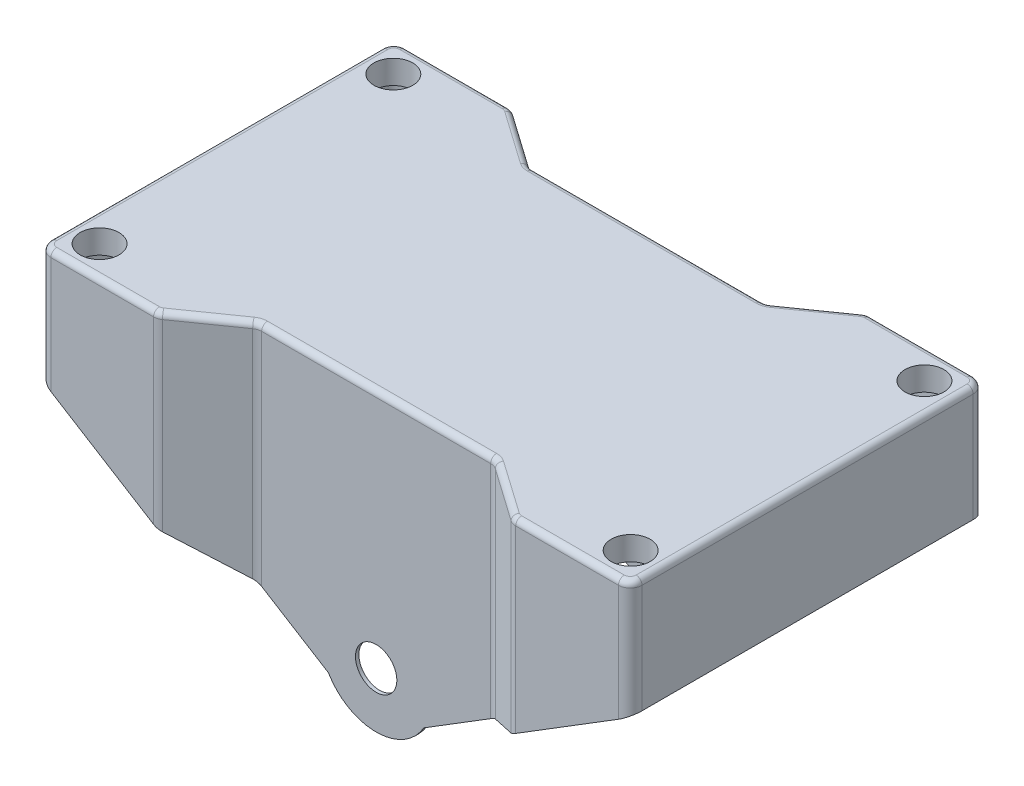
SolidWorks part; units mm, degrees
ref_plane "Front Plane" through (0, 0, 0) normal (0, 0, 1) x (1, 0, 0)
ref_plane "Top Plane" through (0, 0, 0) normal (0, 1, 0) x (1, 0, 0)
ref_plane "Right Plane" through (0, 0, 0) normal (1, 0, 0) x (0, 0, -1)
sketch "Sketch1" plane through (0, 0, 0) normal (0, 1, 0) x (1, 0, 0)
  line L0 (-131.7395, 0) -> (140.8323, 0) construction
  line L1 (0, 62.0007) -> (0, -76.4531) construction
  line L2 (-50, -30) -> (-50, 30)
  line L3 (-50, 30) -> (-30, 30)
  line L4 (-30, 30) -> (-20, 22.9793)
  line L5 (-20, 22.9793) -> (20, 22.9793)
  line L6 (30, 30) -> (20, 22.9793)
  line L7 (50, 30) -> (30, 30)
  line L8 (50, -30) -> (50, 30)
  line L9 (50, -30) -> (30, -30)
  line L10 (30, -30) -> (20, -22.9793)
  line L11 (-20, -22.9793) -> (20, -22.9793)
  line L12 (-30, -30) -> (-20, -22.9793)
  line L13 (-50, -30) -> (-30, -30)
  circle A0 centre (-44.9207, 24.8485) radius 3.2868
  circle A1 centre (-44.9207, -24.8485) radius 3.2868
  circle A2 centre (44.9207, -24.8485) radius 3.2868
  circle A3 centre (44.9207, 24.8485) radius 3.2868
  point P5 (0, -22.9793)
  point P12 (0, 22.9793)
  point P16 (50, 0)
  point P21 (-50, 0)
  dimension "D1" = 50
  dimension "D2" = 20
  dimension "D3" = 20
  dimension "D4" = 30
extrude "Boss-Extrude2" add sketch "Sketch1" against normal blind 50
fillet "Fillet1" radius 2 12 edges at (-50, -25, -30) (-30, -25, -30) (-20, -25, -22.9793) (20, -25, -22.9793) (30, -25, -30) (50, -25, -30) (50, -25, 30) (30, -25, 30) (20, -25, 22.9793) (-20, -25, 22.9793) (-30, -25, 30) (-50, -25, 30)
fillet "Fillet2" radius 1 24 edges at (-30.0294, 0, -29.9071) (-25, 0, -26.4896) (-19.9706, 0, -23.0722) (0, 0, -22.9793) (19.9706, 0, -23.0722) (25, 0, -26.4896) (30.0294, 0, -29.9071) (39.316, 0, -30) (49.4142, 0, -29.4142) (50, 0, 0) (49.4142, 0, 29.4142) (39.316, 0, 30) (30.0294, 0, 29.9071) (25, 0, 26.4896) (19.9706, 0, 23.0722) (0, 0, 22.9793) (-19.9706, 0, 23.0722) (-25, 0, 26.4896) (-30.0294, 0, 29.9071) (-39.316, 0, 30) (-49.4142, 0, 29.4142) (-50, 0, 0) (-49.4142, 0, -29.4142) (-39.316, 0, -30)
sketch "Sketch2" plane through (0, 0, 30) normal (0, 0, 1) x (1, 0, 0)
  line L0 (0, 14.0397) -> (0, -70.6574) construction
  line L2 (-8.0666, -45.3648) -> (-50, -19.3902)
  line L3 (-50, -1) -> (-50, -50) construction
  line L4 (8.0666, -45.3648) -> (50, -19.3902)
  line L5 (-50, -19.3902) -> (-50, -50)
  line L6 (-50, -50) -> (50, -50)
  line L7 (50, -50) -> (50, -19.3902)
  arc A0 (-8.0666, -45.3648) -> (8.0666, -45.3648) centre (0, -40.686) ccw
  circle A1 centre (0, -40.686) radius 3.5
  line M1 (-30.632, -50) -> (-30.632, -1)
  line M3 (-48, -1) -> (-48, -50)
  line M4 (-48, -50) -> (-30.632, -50)
  dimension "D1" = 7
extrude "Cut-Extrude1" cut sketch "Sketch2" against normal blind 70 contours L2 M1 M3 M4 | A0 L2 L6 M1 | A0 L6 L7 L4 | L5 L6 L2 M3 | A1 L0 | L0 A1
sketch "Sketch3" plane through (0, -50, 0) normal (0, -1, 0) x (1, 0, 0)
  line L0 (0, 37.3396) -> (0, -42.0811) construction
  line L1 (0, -42.0811) -> (59.2691, 0) construction
  line L2 (59.2691, 0) -> (-67.1358, 0) construction
  line L3 (-67.1358, 0) -> (-73.386, 28.8264) construction
  line L4 (30.352, 29.4509) -> (20.3535, 22.3999)
  line L5 (-49.4919, 0.6062) -> (-49.4919, 27.4509)
  line L6 (-47.4919, 29.4509) -> (-30.352, 29.4509)
  line L7 (-30.352, 29.4509) -> (-20.3535, 22.3999)
  line L8 (-20.3535, 22.3999) -> (20.3535, 22.3999)
  line L9 (-49.4919, 0.6062) -> (-49.4919, 0)
  line L10 (47.4919, 29.4509) -> (30.352, 29.4509)
  line L11 (49.4919, 0.6062) -> (49.4919, 27.4509)
  line L12 (47.4919, -29.4509) -> (30.352, -29.4509)
  line L13 (49.4919, -0.6062) -> (49.4919, -27.4509)
  line L14 (-20.3535, -22.3999) -> (20.3535, -22.3999)
  line L15 (-30.352, -29.4509) -> (-20.3535, -22.3999)
  line L16 (-47.4919, -29.4509) -> (-30.352, -29.4509)
  line L17 (-49.4919, -0.6062) -> (-49.4919, -27.4509)
  line L18 (30.352, -29.4509) -> (20.3535, -22.3999)
  line L19 (-49.4919, 0.6062) -> (-49.4919, 0)
  line L20 (-49.4919, 0.6062) -> (-49.4919, 27.4509)
  line L21 (-47.4919, 29.4509) -> (-30.352, 29.4509)
  line L22 (-30.352, 29.4509) -> (-20.3535, 22.3999)
  line L23 (-20.3535, 22.3999) -> (20.3535, 22.3999)
  line L24 (30.352, 29.4509) -> (20.3535, 22.3999)
  line L25 (47.4919, 29.4509) -> (30.352, 29.4509)
  line L26 (49.4919, 0.6062) -> (49.4919, 27.4509)
  line L27 (-49.4919, 0) -> (-49.4919, -0.6062)
  line L29 (49.4919, 0.6062) -> (49.4919, -0.6062)
  arc A0 (-49.4919, 27.4509) -> (-47.4919, 29.4509) centre (-47.4919, 27.4509) cw
  arc A1 (49.4919, 27.4509) -> (47.4919, 29.4509) centre (47.4919, 27.4509) ccw
  arc A2 (49.4919, -27.4509) -> (47.4919, -29.4509) centre (47.4919, -27.4509) cw
  arc A3 (-49.4919, -27.4509) -> (-47.4919, -29.4509) centre (-47.4919, -27.4509) ccw
  arc A4 (-49.4919, 27.4509) -> (-47.4919, 29.4509) centre (-47.4919, 27.4509) cw
  arc A5 (49.4919, 27.4509) -> (47.4919, 29.4509) centre (47.4919, 27.4509) ccw
  point P14 (0, 22.3999)
  point P32 (0, -22.3999)
  line M8 (-0.4595, 22.9793) -> (-0.4595, -22.9793)
  line M10 (0.4595, -22.9793) -> (0.4595, 22.9793)
  dimension "D1" = 2
  dimension "D2" = 0
extrude "Cut-Extrude3" cut sketch "Sketch3" against normal blind 46 contours L17 A3 L16 L15 L14 L8 L7 L6 A0 L5 L9 L27 M8 | L14 L8 M8 M10 | A2 L13 L29 L11 A1 L10 L4 L8 L14 L18 L12 M10
